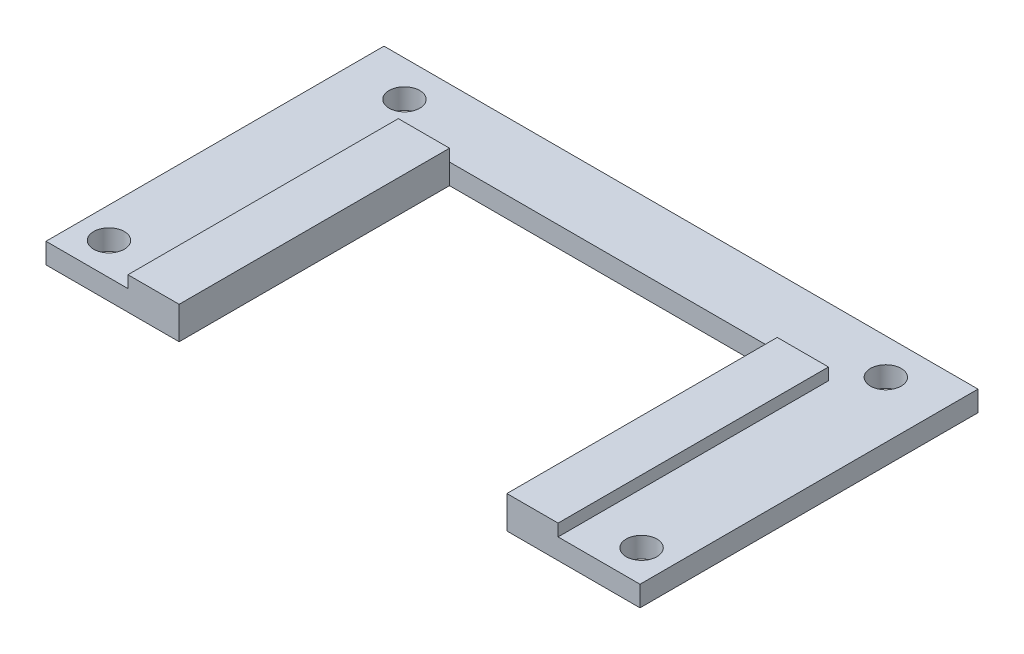
SolidWorks part; units mm, degrees
ref_plane "Front Plane" through (0, 0, 0) normal (0, 0, 1) x (1, 0, 0)
ref_plane "Top Plane" through (0, 0, 0) normal (0, 1, 0) x (1, 0, 0)
ref_plane "Right Plane" through (0, 0, 0) normal (1, 0, 0) x (0, 0, -1)
sketch "Sketch1" plane through (0, 0, 0) normal (0, 1, 0) x (1, 0, 0)
  line L0 (0, 0) -> (52, 0)
  line L1 (0, 0) -> (0, 3.15) construction
  line L2 (52, 0) -> (52, 3.15)
  line L4 (2.5, 0) -> (2.5, 29.5) construction
  line L5 (0, 3.15) -> (2.5, 3.15) construction
  line L6 (0, 0) -> (-3, 0)
  line L7 (-3, 0) -> (-3, 33)
  line L8 (-3, 33) -> (55, 33)
  line L9 (55, 33) -> (55, 0)
  line L10 (55, 0) -> (52, 0)
  line L11 (2.5, 3.15) -> (10, 3.15) construction
  line L12 (10, 0) -> (10, 26.4)
  line L13 (52, 3.15) -> (49.5, 3.15) construction
  line L14 (49.5, 0) -> (49.5, 29.5) construction
  line L15 (49.5, 3.15) -> (42, 3.15) construction
  line L16 (42, 0) -> (42, 26.4)
  line L17 (10, 26.4) -> (42, 26.4)
  circle A0 centre (0, 3.15) radius 1.5
  circle A1 centre (52, 3.15) radius 1.5
  circle A2 centre (2.5, 29.5) radius 1.5
  circle A3 centre (49.5, 29.5) radius 1.5
  dimension "D11" = 3
  dimension "D12" = 3
  dimension "D13" = 3
  dimension "D14" = 3
  dimension "D1" = 52
  dimension "D2" = 3.15
  dimension "D3" = 29.5
  dimension "D4" = 2.5
  dimension "D5" = 7.5
  dimension "D6" = 26.4
  dimension "D7" = 3.15
  dimension "D8" = 29.5
  dimension "D9" = 2.5
  dimension "D10" = 7.5
  dimension "D15" = 3
  dimension "D16" = 3
  dimension "D17" = 33
extrude "Boss-Extrude1" add sketch "Sketch1" along normal blind 2
sketch "Sketch2" plane through (0, 2, 0) normal (0, 1, 0) x (1, 0, 0)
  line L1 (10, 0) -> (5, 0)
  line L2 (10, 0) -> (10, 26.4)
  line L3 (10, 26.4) -> (5, 26.4)
  line L4 (5, 0) -> (5, 26.4)
  line L5 (42, 0) -> (47, 0)
  line L6 (42, 0) -> (42, 26.4)
  line L7 (42, 26.4) -> (47, 26.4)
  line L8 (47, 0) -> (47, 26.4)
  dimension "D1" = 5
  dimension "D2" = 5
  dimension "D3" = 26.4
  dimension "D4" = 26.4
extrude "Boss-Extrude2" add sketch "Sketch2" along normal blind 1.17
